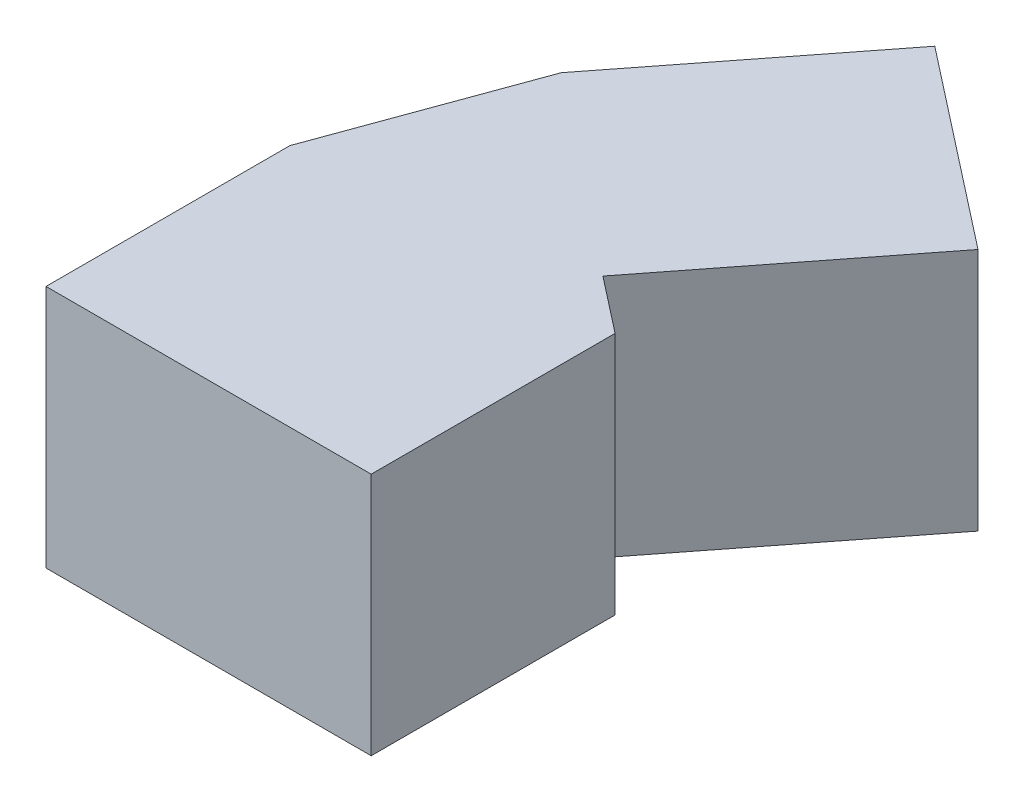
SolidWorks part; units mm, degrees
ref_plane "前视基准面" through (0, 0, 0) normal (0, 0, 1) x (1, 0, 0)
ref_plane "上视基准面" through (0, 0, 0) normal (0, 1, 0) x (1, 0, 0)
ref_plane "右视基准面" through (0, 0, 0) normal (1, 0, 0) x (0, 0, -1)
sketch "草图1" plane through (0, 0, 0) normal (0, 1, 0) x (1, 0, 0)
  line L0 (0, 0) -> (24, 0)
  line L1 (0, 0) -> (0, 18)
  line L2 (24, 0) -> (24, 18)
  line L3 (0, 18) -> (5.3547, 32.6772)
  line L4 (19.888, 21.2127) -> (24, 18)
  line L5 (5.3547, 32.6772) -> (17.4435, 48.1502)
  line L6 (17.4435, 48.1502) -> (32.0301, 36.7539)
  line L7 (32.0301, 36.7539) -> (19.888, 21.2127)
  point P3 (19.8699, 21.2127)
  point P10 (0, 18)
  point P11 (5.3547, 32.6772)
  dimension "D1" = 18
  dimension "D2" = 128
  dimension "D3" = 24
extrude "凸台-拉伸1" add sketch "草图1" along normal blind 18
ref_point "点1"
equation "\"zz_zj\"= 16'中指直径"
equation "\"zz_1cd\"= 24'中指根1节长度"
equation "\"zz_2cd\"= 23'中指根2节长度"
equation "\"zz_3cd\"= 21'中指根3节长度"
equation "\"wz_zj\"= 16'无名指直径"
equation "\"wz_1cd\"= 24'无名指根1节长度"
equation "\"wz_2cd\"= 23'无名指根2节长度"
equation "\"wz_3cd\"= 21'无名指根3节长度"
equation "\"xz_zj\"= 16'小指直径"
equation "\"xz_1cd\"= 22'小指根1节长度"
equation "\"xz_2cd\"= 18'小指根2节长度"
equation "\"xz_3cd\"= 18'小指根3节长度"
equation "\"D1@凸台-拉伸1\"=\"zz_zj\" +2"
